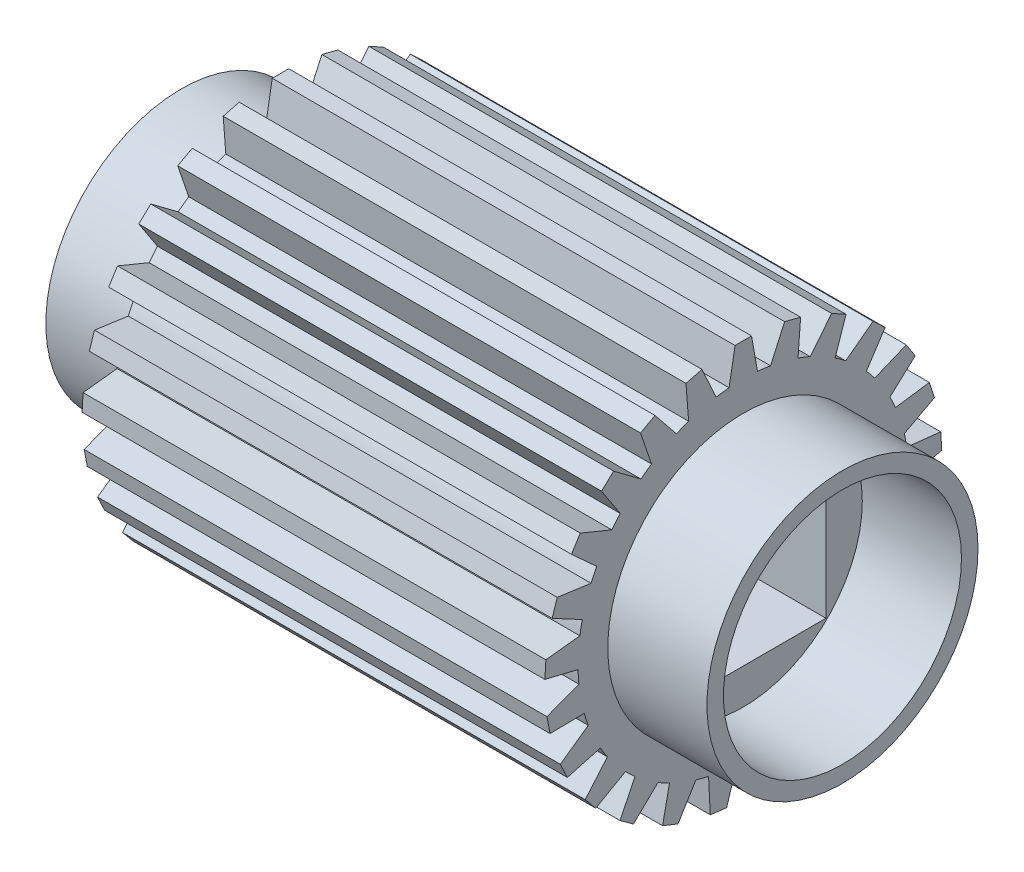
SolidWorks part; units mm, degrees
ref_plane "Front Plane" through (0, 0, 0) normal (0, 0, 1) x (1, 0, 0)
ref_plane "Top Plane" through (0, 0, 0) normal (0, 1, 0) x (1, 0, 0)
ref_plane "Right Plane" through (0, 0, 0) normal (1, 0, 0) x (0, 0, -1)
sketch "Sketch2" plane through (0, 0, 0) normal (1, 0, 0) x (0, 0, -1)
  line L0 (0, 5) -> (0, 6) construction
  line L1 (-0.25, 6) -> (0.25, 6)
  line L2 (-0.25, 6) -> (-0.7008, 3.4435)
  line L3 (-0.7008, 3.4435) -> (0.7008, 3.4435)
  line L4 (0.7008, 3.4435) -> (0.25, 6)
  line L5 (0, 5) -> (0, 3.4435) construction
  arc A0 (0.4296, 4.9815) -> (-0.4296, 4.9815) centre (0, 0) ccw
  point P8 (0, 6)
  dimension "D1" = 10
  dimension "D2" = 1
  dimension "D3" = 0.5
  dimension "D4" = 100
extrude "Boss-Extrude2" add sketch "Sketch2" along normal blind 5 and the other way blind 9 contours L4 A0 L2 L3 | A0 L4 L1 L2
sketch "Sketch3" plane through (0, 0, 0) normal (1, 0, 0) x (0, 0, -1)
  circle A0 centre (0, 0) radius 5
  dimension "D1" = 10
extrude "Boss-Extrude3" add sketch "Sketch3" along normal blind 5 and the other way blind 9
pattern_circular "CirPattern1" count 25 over 360 about axis through (0, 0, 0) along (1, 0, 0) of "Boss-Extrude2"
sketch "Sketch4" plane through (5, 0, 0) normal (1, 0, 0) x (0, 0, -1)
  line L1 (-2.5, -2.5) -> (2.5, -2.5)
  line L2 (-2.5, -2.5) -> (-2.5, 2.5)
  line L3 (-2.5, 2.5) -> (2.5, 2.5)
  line L4 (2.5, -2.5) -> (2.5, 2.5)
  dimension "D1" = 2.5
  dimension "D2" = 5
  dimension "D3" = 5
  dimension "D4" = 2.5
extrude "Cut-Extrude1" cut sketch "Sketch4" against normal blind 18
sketch "Sketch5" plane through (5, 0, 0) normal (1, 0, 0) x (0, 0, -1)
  line L1 (0, -5) -> (0, -6.0359) construction
  circle A0 centre (0, 0) radius 5.5
  arc A1 (-0.1981, -4.9961) -> (0.1981, -4.9961) centre (0, 0) ccw construction
  dimension "D1" = 11
sketch "Sketch6" plane through (5, 0, 0) normal (1, 0, 0) x (0, 0, -1)
  circle A0 centre (0, 0) radius 4.1
  circle A1 centre (0, 0) radius 3.6
  circle A2 centre (0, 0) radius 4.1 construction
  dimension "D1" = 0.5
  dimension "D2" = 0
extrude "Boss-Extrude4" add sketch "Sketch6" along normal blind 3 and the other way blind 17
sketch "Sketch7" plane through (5, 0, 0) normal (1, 0, 0) x (0, 0, -1)
  line L0 (-2.5, 2.5) -> (-2.5, -2.5) construction
  line L1 (-2.5, 2.5) -> (2.5, 2.5)
  line L2 (-2.5, 2.5) -> (-2.5, -2.5216)
  line L3 (-2.5, -2.5216) -> (2.5, -2.5216)
  line L4 (2.5, 2.5) -> (2.5, -2.5216)
  line L5 (2.5, -2.5) -> (2.5, 2.5) construction
  line L6 (2.5, 2.5) -> (-2.5, 2.5) construction
  dimension "D1" = 0
  dimension "D2" = 0
extrude "Cut-Extrude2" cut sketch "Sketch7" against normal blind 20 and the other way blind 10
